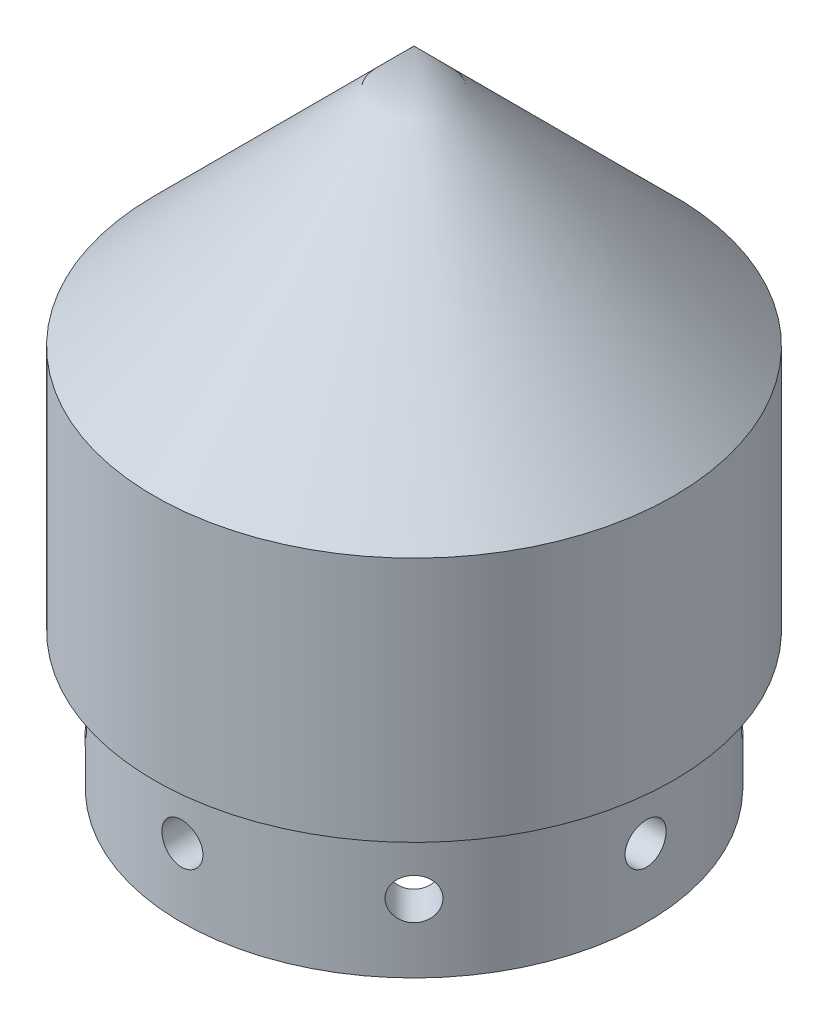
SolidWorks part; units mm, degrees
ref_plane "Front Plane" through (0, 0, 0) normal (0, 0, 1) x (1, 0, 0)
ref_plane "Top Plane" through (0, 0, 0) normal (0, 1, 0) x (1, 0, 0)
ref_plane "Right Plane" through (0, 0, 0) normal (1, 0, 0) x (0, 0, -1)
sketch "Sketch2" plane through (0, 0, 0) normal (0, 0, 1) x (1, 0, 0)
  line L0 (17, 0) -> (17, 10)
  line L1 (17, 10) -> (19, 10)
  line L2 (19, 10) -> (19, 28)
  line L3 (19, 28) -> (0, 47)
  line L4 (14, 0) -> (14, 13)
  line L5 (14, 13) -> (16, 13)
  line L6 (16, 13) -> (16, 26.7574)
  line L7 (16, 26.7574) -> (0, 42.7574)
  line L8 (14, 0) -> (17, 0)
  line L9 (0, 47) -> (0, 42.7574)
  line L10 (19, 28) -> (2.1213, 44.8787) construction
  line L11 (0, 26.1127) -> (0, -10.4704) construction
  dimension "D1" = 19
  dimension "31" = 17
  dimension "D2" = 225
  dimension "D3" = 10
  dimension "D4" = 18
  dimension "D5" = 3
revolve "Revolve1" add sketch "Sketch2" angle 360 about L11
sketch "Sketch3" plane through (0, 0, 0) normal (0, 0, 1) x (1, 0, 0)
  circle A0 centre (0, 5) radius 1.5
  point P2 (0, 0)
  dimension "D1" = 3
  dimension "D2" = 5
extrude "Cut-Extrude1" cut sketch "Sketch3" against normal through all
pattern_circular "CirPattern1" count 8 over 360 about axis through (0, 26.1127, 0) along (0, 1, 0) of "Cut-Extrude1"
